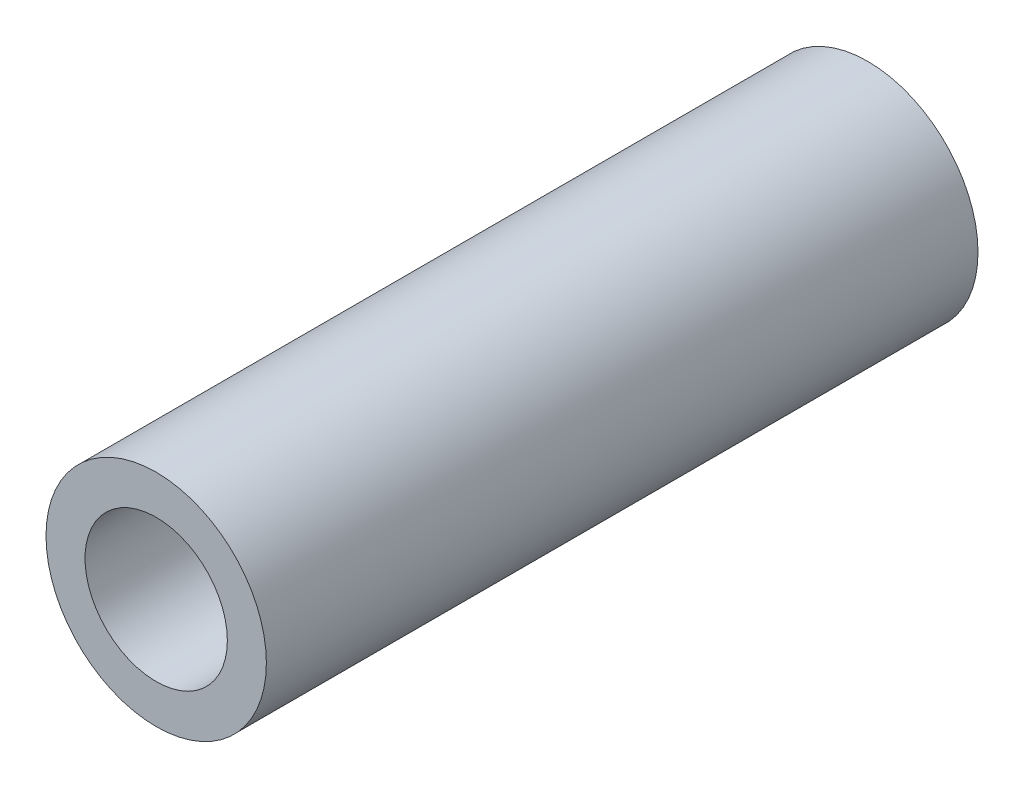
SolidWorks part; units mm, degrees
ref_plane "Front Plane" through (0, 0, 0) normal (0, 0, 1) x (1, 0, 0)
ref_plane "Top Plane" through (0, 0, 0) normal (0, 1, 0) x (1, 0, 0)
ref_plane "Right Plane" through (0, 0, 0) normal (1, 0, 0) x (0, 0, -1)
sketch "Sketch1" plane through (0, 0, 0) normal (0, 0, 1) x (1, 0, 0)
  circle A0 centre (0, 0) radius 2.4
  circle A1 centre (0, 0) radius 1.55
extrude "Boss-Extrude1" add sketch "Sketch1" along normal blind 15.5
